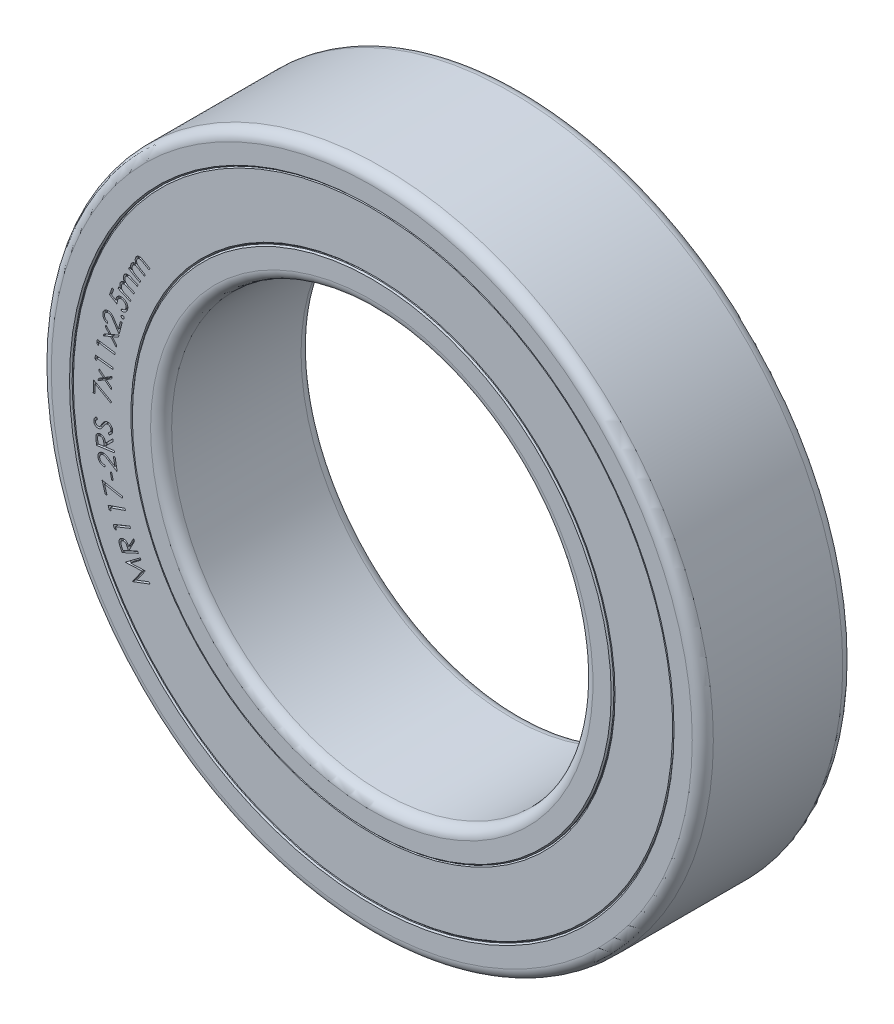
SolidWorks part; units mm, degrees
material "AISI 316 Annealed Stainless Steel Bar (SS)"
ref_plane "Front" through (0, 0, 0) normal (0, 0, 1) x (1, 0, 0)
ref_plane "Top" through (0, 0, 0) normal (0, 1, 0) x (1, 0, 0)
ref_plane "Right" through (0, 0, 0) normal (1, 0, 0) x (0, 0, -1)
sketch "LAYOUT R" plane through (0, 0, 0) normal (1, 0, 0) x (0, 0, -1)
  line L0 (-1.25, 3.5) -> (1.25, 3.5)
  line L1 (1.25, -5.5) -> (-1.25, -5.5) construction
  line L2 (1.25, -5.5) -> (1.25, 5.5) construction
  line L3 (1.25, 5.5) -> (-1.25, 5.5)
  line L4 (-1.25, -5.5) -> (-1.25, 5.5) construction
  line L5 (1.25, -5.5) -> (-1.25, 5.5) construction
  line L6 (1.25, 5.5) -> (-1.25, -5.5) construction
  line L7 (-1.25, 4) -> (1.25, 4)
  line L8 (-1.25, 5) -> (1.25, 5)
  line L11 (-17.5, 0) -> (17.5, 0) construction
  line L12 (-1.25, 5.5) -> (-1.25, 5)
  line L13 (1.25, 5.5) -> (1.25, 5)
  line L14 (-1.25, 5) -> (-1.25, 4)
  line L15 (1.25, 5) -> (1.25, 4)
  line L16 (-1.25, 4) -> (-1.25, 3.5)
  line L17 (1.25, 4) -> (1.25, 3.5)
  line L18 (-1.23, 5) -> (-1.23, 4)
  line L19 (1.23, 5) -> (1.23, 4)
  point P0 (0, 0)
  point P15 (0, 0)
  dimension "D1" = 2.5
  dimension "D2" = 11
  dimension "D3" = 3.5
  dimension "D6" = 0.02
  dimension "D7" = 0.02
  dimension "D4" = 4
  dimension "D5" = 5
sketch "Sketch R, INNER BODY" plane through (0, 0, 0) normal (1, 0, 0) x (0, 0, -1)
  line L0 (-1.25, 3.5) -> (1.25, 3.5) construction
  line L2 (-1.25, 4) -> (1.25, 4) construction
  line L4 (-1.25, 3.5) -> (1.25, 3.5)
  line L6 (-1.25, 4) -> (1.25, 4)
  line L8 (1.25, 4) -> (1.25, 3.5) construction
  line L9 (-1.25, 4) -> (-1.25, 3.5) construction
  line L10 (1.25, 4) -> (1.25, 3.5)
  line L11 (-1.25, 4) -> (-1.25, 3.5)
  line L12 (-17.5, 0) -> (17.5, 0) construction
  line L13 (-17.5, 0) -> (17.5, 0) construction
sketch "Sketch R, OUTER BODY" plane through (0, 0, 0) normal (1, 0, 0) x (0, 0, -1)
  line L2 (-1.25, 5) -> (1.25, 5) construction
  line L3 (1.25, 5.5) -> (-1.25, 5.5) construction
  line L6 (-1.25, 5) -> (1.25, 5)
  line L7 (1.25, 5.5) -> (-1.25, 5.5)
  line L8 (-17.5, 0) -> (17.5, 0) construction
  line L9 (-17.5, 0) -> (17.5, 0) construction
  line L10 (1.25, 5.5) -> (1.25, 5) construction
  line L11 (-1.25, 5.5) -> (-1.25, 5) construction
  line L12 (1.25, 5.5) -> (1.25, 5)
  line L13 (-1.25, 5.5) -> (-1.25, 5)
sketch "Sketch R, SEAL FACES" plane through (0, 0, 0) normal (1, 0, 0) x (0, 0, -1)
  line L0 (-17.5, 0) -> (17.5, 0) construction
  line L1 (-17.5, 0) -> (17.5, 0) construction
  line L3 (-1.25, 4) -> (1.25, 4) construction
  line L5 (-1.25, 5) -> (1.25, 5) construction
  line L7 (-1.23, 4) -> (1.23, 4)
  line L9 (-1.23, 5) -> (1.23, 5)
  line L10 (1.23, 5) -> (1.23, 4) construction
  line L11 (-1.23, 5) -> (-1.23, 4) construction
  line L12 (1.23, 5) -> (1.23, 4)
  line L13 (-1.23, 5) -> (-1.23, 4)
revolve "Revolve INNER BODY" add sketch "Sketch R, INNER BODY" angle 360 about L13
fillet "Fillet INNER BODY" radius 0.175 2 edges at (3.5, 0, 1.25) (3.5, 0, -1.25)
chamfer "Chamfer INNER BODY" distance 0.022 angle 45 2 edges at (4, 0, -1.25) (4, 0, 1.25)
revolve "Revolve OUTER BODY" add sketch "Sketch R, OUTER BODY" angle 360 about L9
fillet "Fillet OUTER BODY" radius 0.175 2 edges at (5.5, 0, -1.25) (5.5, 0, 1.25)
chamfer "Chamfer OUTER BODY" distance 0.022 angle 45 2 edges at (5, 0, 1.25) (5, 0, -1.25)
revolve "Revolve SEALS" add sketch "Sketch R, SEAL FACES" angle 360 about L1
chamfer "Chamfer SEALS" distance 0.022 angle 45 4 edges at (4, 0, -1.23) (5, 0, -1.23) (5, 0, 1.23) (4, 0, 1.23)
sketch "Sketch TEXT RADIUS 1 — MANUALLY ASSIGN TEXT AND FONT SIZE (FROM EQUATIONS)" plane through (0, 0, 1.23) normal (0, 0, 1) x (1, 0, 0)
  circle A0 centre (0, 0) radius 4.35 construction
  text T0 "MR117-2RS  7x11x2.5mm" font "Century Gothic" height 0.3
  dimension "D1" = 8.7
extrude "Cut-Extrude SEAL LABEL 1" cut sketch "Sketch TEXT RADIUS 1 — MANUALLY ASSIGN TEXT AND FONT SIZE (FROM EQUATIONS)" against normal blind 0.05
sketch "Sketch TEXT RADIUS 2 — MANUALLY ASSIGN TEXT AND FONT SIZE (FROM EQUATIONS)" plane through (0, 0, -1.23) normal (0, 0, -1) x (-1, 0, 0)
  circle A0 centre (0, 0) radius 4.35 construction
  text T0 "MR117-2RS  7x11x2.5mm" font "Century Gothic" height 0.3
  dimension "D1" = 8.7
extrude "Cut-Extrude SEAL LABEL 2" cut sketch "Sketch TEXT RADIUS 2 — MANUALLY ASSIGN TEXT AND FONT SIZE (FROM EQUATIONS)" against normal blind 0.05
equation "\"_i__BORE\"= 7"
equation "\"_i__OUTSIDE_DIAMETER\"= 11"
equation "\"_i__WIDTH\"= 2.5"
equation "\"_i_optional__TEXT_RADIUS_ADJUSTMENT\"= 0"
equation "\"_output__FONT_SIZE_mm\"= \"BODY_SPAN__SEAL__OF_RADIUS\" * \"param__FONT_SIZE_RATIO\"'MANUALLY ASSIGN TO FONT"
equation "\"BODY__HALF_WIDTH\"= \"_i__WIDTH\" / 2"
equation "\"BODY_SPAN___OF_DIAMETER\"= \"_i__OUTSIDE_DIAMETER\" - \"_i__BORE\""
equation "\"BODY_SPAN___OF_RADIUS\"= \"BODY_SPAN___OF_DIAMETER\" / 2"
equation "\"BODY_SPAN__BORE_AND_OD__OF RADIUS\"= ( \"BODY_SPAN___OF_RADIUS\" - \"BODY_SPAN__SEAL__OF_RADIUS\" ) / 2"
equation "\"BODY_SPAN__SEAL__OF_RADIUS\"= \"BODY_SPAN___OF_RADIUS\" * \"param__SEAL_PANEL_SPAN__RATIO_OF_BODY_RADIAN\""
equation "\"BORE__RADIUS\"= \"_i__BORE\" / 2"
equation "\"CORNER_RADII\"= \"_i__WIDTH\" * \"param__CORNER_RADII__ISO_MAX_RATIO_TO_WIDTH\""
equation "\"param__CORNER_RADII__ISO_MAX_RATIO_TO_WIDTH\"= 0.07'WHERE WIDTH IS LESS THAN DIAMETER"
equation "\"param__FONT_SIZE_RATIO\"= 0.3"
equation "\"param__SEAL_FACE_INSET__RATIO_OF_WIDTH\"= .01"
equation "\"param__SEAL_PANEL_SPAN__RATIO_OF_BODY_RADIAN\"= 0.5"
equation "\"param__SIDE_CHAMFERS__RATIO_TO_OD\"= 1 / 500"
equation "\"RING_INNER__OUTSIDE_RADIUS\"= \"BORE__RADIUS\" + \"BODY_SPAN__BORE_AND_OD__OF RADIUS\""
equation "\"RING_OUTER__OUTSIDE_RADIUS\"= ( \"_i__OUTSIDE_DIAMETER\" / 2 ) - \"BODY_SPAN__BORE_AND_OD__OF RADIUS\""
equation "\"SEAL_FACE_INSET\"= \"_i__WIDTH\" * \"param__SEAL_FACE_INSET__RATIO_OF_WIDTH\""
equation "\"SIDE_FACE_AND_SEAL_CHAMFERS\"= \"_i__OUTSIDE_DIAMETER\" * \"param__SIDE_CHAMFERS__RATIO_TO_OD\""
equation "\"TEXT_RADIUS\"= \"_i__BORE\" + ( \"BODY_SPAN___OF_DIAMETER\" / 2 ) - \"_output__FONT_SIZE_mm\" + \"_i_optional__TEXT_RADIUS_ADJUSTMENT\""
equation "\"D1@Chamfer INNER BODY\"=\"SIDE_FACE_AND_SEAL_CHAMFERS\""
equation "\"D1@Chamfer OUTER BODY\"=\"SIDE_FACE_AND_SEAL_CHAMFERS\""
equation "\"D1@Chamfer SEALS\"=\"SIDE_FACE_AND_SEAL_CHAMFERS\""
equation "\"D1@Fillet INNER BODY\"=\"CORNER_RADII\""
equation "\"D1@Fillet OUTER BODY\"=\"CORNER_RADII\""
equation "\"D1@LAYOUT R\"=\"_i__WIDTH\""
equation "\"D1@Sketch TEXT RADIUS 1 — MANUALLY ASSIGN TEXT AND FONT SIZE (FROM EQUATIONS)\" = \"TEXT_RADIUS\""
equation "\"D1@Sketch TEXT RADIUS 2 — MANUALLY ASSIGN TEXT AND FONT SIZE (FROM EQUATIONS)\" = \"TEXT_RADIUS\""
equation "\"D2@LAYOUT R\"=\"_i__OUTSIDE_DIAMETER\""
equation "\"D3@LAYOUT R\"=\"BORE__RADIUS\""
equation "\"D4@LAYOUT R\"=\"RING_INNER__OUTSIDE_RADIUS\""
equation "\"D5@LAYOUT R\"=\"RING_OUTER__OUTSIDE_RADIUS\""
